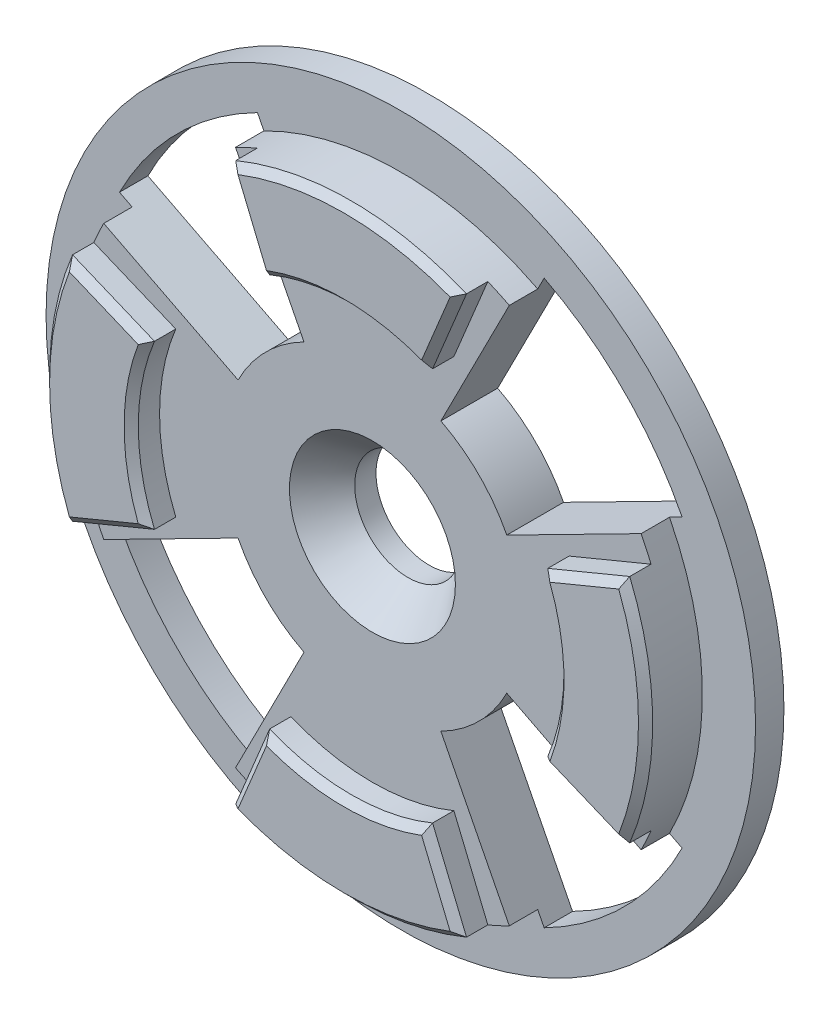
SolidWorks part; units mm, degrees
ref_plane "Front Plane" through (0, 0, 0) normal (0, 0, 1) x (1, 0, 0)
ref_plane "Top Plane" through (0, 0, 0) normal (0, 1, 0) x (1, 0, 0)
ref_plane "Right Plane" through (0, 0, 0) normal (1, 0, 0) x (0, 0, -1)
sketch "Sketch1" plane through (0, 0, 0) normal (0, 0, 1) x (1, 0, 0)
  circle A0 centre (0, 0) radius 10
  dimension "D1" = 20
extrude "Boss-Extrude1" add sketch "Sketch1" along normal blind 0.8
sketch "Sketch2" plane through (0, 0, 0.8) normal (0, 0, 1) x (1, 0, 0)
  circle A0 centre (0, 0) radius 8 construction
  circle A3 centre (0, -8) radius 1.1
  dimension "D1" = 16
extrude "Cut-Extrude1" cut sketch "Sketch2" against normal blind 10
sketch "Sketch3" plane through (0, 0, 0.8) normal (0, 0, 1) x (1, 0, 0)
  arc A0 (1.0977, -8.4288) -> (-1.0977, -8.4288) centre (0, 0) ccw
  arc A1 (1.0977, -8.4288) -> (-1.0977, -8.4288) centre (0, -8) ccw
extrude "Boss-Extrude2" add sketch "Sketch3" along normal blind 0.8
sketch "Sketch4" plane through (0, 0, 1.6) normal (0, 0, 1) x (1, 0, 0)
  circle A0 centre (0, 0) radius 1.5
extrude "Cut-Extrude2" cut sketch "Sketch4" against normal blind 10
chamfer "Chamfer1" distance 1 angle 40 1 edges at (1.5, 0, 1.6)
sketch "Sketch6" plane through (0, 0, 0.8) normal (0, 0, 1) x (1, 0, 0)
sketch "Sketch7" plane through (0, 0, 0.8) normal (0, 0, 1) x (1, 0, 0)
  circle A0 centre (0, -8) radius 1.1
extrude "Boss-Extrude3" add sketch "Sketch7" against normal up to surface (0.8 mm away) up to face at (1.5, 0, 0)
sketch "Sketch8" plane through (0, 0, 0.8) normal (0, 0, 1) x (1, 0, 0)
  arc A0 (1.0977, -8.4288) -> (-1.0977, -8.4288) centre (0, -8) ccw
  arc A1 (-1.0977, -8.4288) -> (1.0977, -8.4288) centre (0, 0) ccw
extrude "Boss-Extrude4" add sketch "Sketch8" along normal up to surface (0.8 mm away) up to face at (2.3391, 0, 1.6)
sketch "Sketch9" plane through (0, 0, 1.6) normal (0, 0, 1) x (1, 0, 0)
  line L0 (0, 0) -> (4.6103, 4.6103) construction
  line L1 (0, 0) -> (-4.6103, -4.6103) construction
  circle A0 centre (-4.6103, -4.6103) radius 0.755
  circle A1 centre (4.6103, 4.6103) radius 0.755
  dimension "D3" = 1.51
  dimension "D4" = 1.51
  dimension "D1" = 6.52
  dimension "D2" = 6.52
extrude "Cut-Extrude3" cut sketch "Sketch9" against normal through all both and the other way through all
sketch "Sketch10" plane through (0, 0, 1.6) normal (0, 0, 1) x (1, 0, 0)
  circle A0 centre (4.6103, 4.6103) radius 1.5
extrude "Cut-Extrude4" cut sketch "Sketch10" against normal through all both and the other way through all
sketch "Sketch11" plane through (0, 0, 1.6) normal (0, 0, 1) x (1, 0, 0)
  line L0 (4.6103, 4.6103) -> (6.4552, 6.4552)
extrude "Cut-Extrude-Thin1" cut sketch "Sketch11" against normal blind 0.8 and the other way through all thin thin type mid plane wall 0.6
sketch "Sketch12" plane through (0, 0, 1.6) normal (0, 0, 1) x (1, 0, 0)
  line L0 (0, 0) -> (8.5, 0) construction
  line L1 (0, 0) -> (-8.5, 0) construction
  line L2 (0, 0) -> (0, 8.5) construction
  line L3 (0, 0) -> (0, -8.5) construction
  line L4 (0, 0) -> (-6.0104, 6.0104) construction
  line L5 (0, 0) -> (-4.9497, -4.9497) construction
  line L6 (0, 0) -> (6.0104, -6.0104) construction
  line L7 (0, 0) -> (6.0104, 6.0104) construction
  line L8 (5.5433, 2.2961) -> (7.853, 3.2528)
  line L9 (5.5433, -2.2961) -> (7.853, -3.2528)
  line L10 (2.2961, -5.5433) -> (3.2528, -7.853)
  line L11 (-2.2961, -5.5433) -> (-3.2528, -7.853)
  line L12 (-5.5433, -2.2961) -> (-7.853, -3.2528)
  line L13 (-5.5433, 2.2961) -> (-7.853, 3.2528)
  line L14 (-2.2961, 5.5433) -> (-3.2528, 7.853)
  line L15 (2.2961, 5.5433) -> (3.2528, 7.853)
  arc A0 (-3.2528, -7.853) -> (3.2528, -7.853) centre (0, 0) ccw
  arc A2 (-7.853, 3.2528) -> (-7.853, -3.2528) centre (0, 0) ccw
  arc A4 (3.2528, 7.853) -> (-3.2528, 7.853) centre (0, 0) ccw
  arc A6 (7.853, -3.2528) -> (7.853, 3.2528) centre (0, 0) ccw
  arc A8 (5.5433, -2.2961) -> (5.5433, 2.2961) centre (0, 0) ccw
  arc A9 (2.2961, 5.5433) -> (-2.2961, 5.5433) centre (0, 0) ccw
  arc A10 (-5.5433, 2.2961) -> (-5.5433, -2.2961) centre (0, 0) ccw
  arc A11 (-2.2961, -5.5433) -> (2.2961, -5.5433) centre (0, 0) ccw
  dimension "D2" = 17
  dimension "D3" = 22.5
  dimension "D4" = 22.5
  dimension "D5" = 22.5
  dimension "D6" = 22.5
  dimension "D7" = 22.5
  dimension "D8" = 22.5
  dimension "D9" = 22.5
  dimension "D10" = 22.5
extrude "Boss-Extrude5" add sketch "Sketch12" along normal blind 0.8
sketch "Sketch14" plane through (0, 0, 1.6) normal (0, 0, 1) x (1, 0, 0)
  line L0 (-4.6103, -4.6103) -> (4.6103, -4.6103) construction
  line L1 (-4.6103, -4.6103) -> (-4.6103, 4.6103) construction
  line L2 (4.6103, 4.6103) -> (4.6103, -4.6103) construction
  line L3 (4.6103, 4.6103) -> (-4.6103, 4.6103) construction
  circle A0 centre (4.6103, -4.6103) radius 0.755
  circle A1 centre (-4.6103, 4.6103) radius 0.755
  circle A2 centre (-4.6103, -4.6103) radius 0.755 construction
extrude "Cut-Extrude5" cut sketch "Sketch14" against normal blind 10
chamfer "Chamfer2" distance 0.2 angle 45 16 edges at (2.7745, 6.6981, 2.4) (0, 6, 2.4) (-2.7745, 6.6981, 2.4) (0, 8.5, 2.4) (-6.6981, -2.7745, 2.4) (-8.5, 0, 2.4) (-6.6981, 2.7745, 2.4) (-6, 0, 2.4) (2.7745, -6.6981, 2.4) (0, -8.5, 2.4) (-2.7745, -6.6981, 2.4) (0, -6, 2.4) (6.6981, -2.7745, 2.4) (6, 0, 2.4) (6.6981, 2.7745, 2.4) (8.5, 0, 2.4)
sketch "Sketch15" plane through (0, 0, 1.6) normal (0, 0, 1) x (1, 0, 0)
  line L0 (0, 0) -> (6.0104, -6.0104) construction
  line L1 (0, 0) -> (7.5736, -3.8589) construction
  line L2 (0, 0) -> (3.8589, -7.5736) construction
  line L3 (0, 0) -> (-6.0104, -6.0104) construction
  line L4 (0, 0) -> (6.0104, 6.0104) construction
  line L5 (0, 0) -> (-6.0104, 6.0104) construction
  line L6 (0, 0) -> (-3.8589, 7.5736) construction
  line L7 (0, 0) -> (-7.5736, 3.8589) construction
  line L8 (0, 0) -> (-7.5736, -3.8589) construction
  line L9 (0, 0) -> (-3.8589, -7.5736) construction
  line L10 (0, 0) -> (3.8589, 7.5736) construction
  line L11 (0, 0) -> (7.5736, 3.8589) construction
  line L12 (-7.5736, -3.8589) -> (-3.7868, -1.9295)
  line L13 (-3.8589, -7.5736) -> (-1.9295, -3.7868)
  line L14 (-7.5736, 3.8589) -> (-3.7868, 1.9295)
  line L15 (-3.8589, 7.5736) -> (-1.9295, 3.7868)
  line L16 (3.8589, 7.5736) -> (1.9295, 3.7868)
  line L17 (7.5736, 3.8589) -> (3.7868, 1.9295)
  line L18 (7.5736, -3.8589) -> (3.7868, -1.9295)
  line L19 (3.8589, -7.5736) -> (1.9295, -3.7868)
  line L20 (7.5736, -3.8589) -> (7.93, -4.0405)
  line L21 (3.8589, -7.5736) -> (4.0405, -7.93)
  line L22 (-3.8589, -7.5736) -> (-4.0405, -7.93)
  line L23 (-7.5736, -3.8589) -> (-7.93, -4.0405)
  line L24 (-7.5736, 3.8589) -> (-7.93, 4.0405)
  line L25 (-3.8589, 7.5736) -> (-4.0405, 7.93)
  line L26 (3.8589, 7.5736) -> (4.0405, 7.93)
  line L27 (7.5736, 3.8589) -> (7.93, 4.0405)
  arc A0 (3.2528, -7.853) -> (7.853, -3.2528) centre (0, 0) ccw construction
  arc A1 (5.7945, 6.2188) -> (6.2188, 5.7945) centre (0, 0) ccw construction
  arc A2 (-7.853, -3.2528) -> (-3.2528, -7.853) centre (0, 0) ccw construction
  arc A3 (-3.2528, 7.853) -> (-7.853, 3.2528) centre (0, 0) ccw construction
  arc A4 (7.853, 3.2528) -> (6.2188, 5.7945) centre (0, 0) ccw construction
  arc A13 (1.9295, -3.7868) -> (3.7868, -1.9295) centre (0, 0) ccw
  arc A14 (-7.93, -4.0405) -> (-4.0405, -7.93) centre (0, 0) ccw
  arc A15 (-4.0405, 7.93) -> (-7.93, 4.0405) centre (0, 0) ccw
  arc A16 (7.93, 4.0405) -> (4.0405, 7.93) centre (0, 0) ccw
  arc A17 (4.0405, -7.93) -> (7.93, -4.0405) centre (0, 0) ccw
  arc A18 (-3.7868, -1.9295) -> (-1.9295, -3.7868) centre (0, 0) ccw
  arc A19 (-1.9295, 3.7868) -> (-3.7868, 1.9295) centre (0, 0) ccw
  arc A20 (3.7868, 1.9295) -> (1.9295, 3.7868) centre (0, 0) ccw
  dimension "D5" = 8.5
  dimension "D6" = 8.9
  dimension "D1" = 18
  dimension "D2" = 18
  dimension "D3" = 18
  dimension "D4" = 18
extrude "Cut-Extrude6" cut sketch "Sketch15" against normal blind 10
